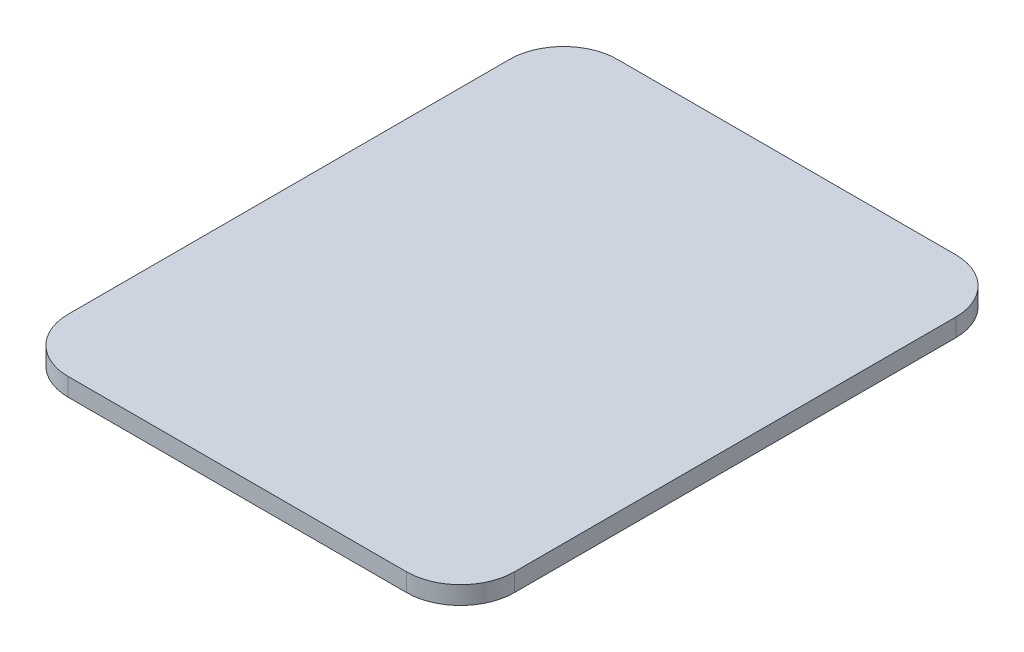
SolidWorks part; units mm, degrees
ref_plane "Front Plane" through (0, 0, 0) normal (0, 0, 1) x (1, 0, 0)
ref_plane "Top Plane" through (0, 0, 0) normal (0, 1, 0) x (1, 0, 0)
ref_plane "Right Plane" through (0, 0, 0) normal (1, 0, 0) x (0, 0, -1)
sketch "Sketch2" plane through (0, 0, 0) normal (0, 1, 0) x (1, 0, 0)
  line L0 (-46.2289, -76.7065) -> (47.6761, -76.7065)
  line L1 (-61.1889, -61.7465) -> (-61.1889, 60.7335)
  line L2 (-46.2289, 75.6935) -> (47.6761, 75.6935)
  line L3 (62.6361, -61.7465) -> (62.6361, 60.7335)
  line L4 (-61.1889, -76.7065) -> (62.6361, 75.6935) construction
  line L5 (-61.1889, 75.6935) -> (62.6361, -76.7065) construction
  arc A0 (47.6761, 75.6935) -> (62.6361, 60.7335) centre (47.6761, 60.7335) cw
  arc A1 (-61.1889, 60.7335) -> (-46.2289, 75.6935) centre (-46.2289, 60.7335) cw
  arc A2 (-46.2289, -76.7065) -> (-61.1889, -61.7465) centre (-46.2289, -61.7465) cw
  arc A3 (47.6761, -76.7065) -> (62.6361, -61.7465) centre (47.6761, -61.7465) ccw
  point P0 (0.7236, -0.5065)
extrude "Boss-Extrude1" add sketch "Sketch2" along normal blind 5
sketch "Sketch3" plane through (0, 5, 0) normal (0, 1, 0) x (1, 0, 0)
  line L0 (62.6361, -61.7465) -> (62.6361, 60.7335) construction
  line L5 (36.5711, 49.6435) -> (50.5711, 49.6435)
  line L6 (36.5711, 49.6435) -> (36.5711, 63.6435)
  line L7 (36.5711, 63.6435) -> (50.5711, 63.6435)
  line L8 (50.5711, 49.6435) -> (50.5711, 63.6435)
  line L9 (36.5711, 49.6435) -> (50.5711, 63.6435) construction
  line L10 (36.5711, 63.6435) -> (50.5711, 49.6435) construction
  line L11 (47.6761, 75.6935) -> (-46.2289, 75.6935) construction
  line L12 (36.5711, 56.6435) -> (31.5211, 56.6435) construction
  line L13 (17.5211, 49.6435) -> (31.5211, 49.6435)
  line L14 (17.5211, 49.6435) -> (17.5211, 63.6435)
  line L15 (17.5211, 63.6435) -> (31.5211, 63.6435)
  line L16 (31.5211, 49.6435) -> (31.5211, 63.6435)
  line L17 (17.5211, 56.6435) -> (12.4711, 56.6435) construction
  line L18 (-1.5289, 49.6435) -> (12.4711, 49.6435)
  line L19 (-1.5289, 49.6435) -> (-1.5289, 63.6435)
  line L20 (-1.5289, 63.6435) -> (12.4711, 63.6435)
  line L21 (12.4711, 49.6435) -> (12.4711, 63.6435)
  line L22 (-1.5289, 56.6435) -> (-6.5789, 56.6435) construction
  line L23 (-20.5789, 49.6435) -> (-6.5789, 49.6435)
  line L24 (-20.5789, 49.6435) -> (-20.5789, 63.6435)
  line L25 (-20.5789, 63.6435) -> (-6.5789, 63.6435)
  line L26 (-6.5789, 49.6435) -> (-6.5789, 63.6435)
  line L27 (-13.5789, 49.6435) -> (-13.5789, 20.4935) construction
  line L28 (-49.1539, 49.6435) -> (-35.1539, 49.6435)
  line L29 (-49.1539, 49.6435) -> (-49.1539, 63.6435)
  line L30 (-49.1539, 63.6435) -> (-35.1539, 63.6435)
  line L31 (-35.1539, 49.6435) -> (-35.1539, 63.6435)
  line L32 (43.5711, 49.6435) -> (43.5711, 20.4935) construction
  line L33 (-13.5789, 35.0685) -> (43.5711, 35.0685) construction
  line L34 (-13.5789, 35.0685) -> (43.2529, 35.0685) construction
  line L35 (36.2246, 28.0266) -> (50.2246, 28.0266)
  line L36 (36.2246, 28.0266) -> (36.2246, 42.0266)
  line L37 (36.2246, 42.0266) -> (50.2246, 42.0266)
  line L38 (50.2246, 28.0266) -> (50.2246, 42.0266)
  line L39 (36.2246, 28.0266) -> (50.2246, 42.0266) construction
  line L40 (36.2246, 42.0266) -> (50.2246, 28.0266) construction
  line L41 (36.2246, 35.0266) -> (31.1746, 35.0266) construction
  line L42 (17.1746, 28.0266) -> (31.1746, 28.0266)
  line L43 (17.1746, 28.0266) -> (17.1746, 42.0266)
  line L44 (17.1746, 42.0266) -> (31.1746, 42.0266)
  line L45 (31.1746, 28.0266) -> (31.1746, 42.0266)
  line L46 (17.1746, 35.0266) -> (12.1246, 35.0266) construction
  line L47 (-1.8754, 28.0266) -> (12.1246, 28.0266)
  line L48 (-1.8754, 28.0266) -> (-1.8754, 42.0266)
  line L49 (-1.8754, 42.0266) -> (12.1246, 42.0266)
  line L50 (12.1246, 28.0266) -> (12.1246, 42.0266)
  line L51 (-1.8754, 35.0266) -> (-6.9254, 35.0266) construction
  line L52 (-20.9254, 28.335) -> (-6.9254, 28.335)
  line L53 (-20.9254, 28.335) -> (-20.9254, 42.335)
  line L54 (-20.9254, 42.335) -> (-6.9254, 42.335)
  line L55 (-6.9254, 28.335) -> (-6.9254, 42.335)
  point P0 (43.5711, 56.6435)
  point P39 (43.2246, 35.0266)
  dimension "D1" = 14
  dimension "D2" = 14
  dimension "D3" = 12.065
  dimension "D4" = 12.05
  dimension "D5" = 5.05
  dimension "D6" = 5.05
  dimension "D7" = 5.05
  dimension "D8" = 14
  dimension "D9" = 14
  dimension "D10" = 14
  dimension "D11" = 12.05
  dimension "D12" = 12.05
  dimension "D13" = 12.05
  dimension "D14" = 14
  dimension "D15" = 14
  dimension "D16" = 14
  dimension "D17" = 14
  dimension "D18" = 14
  dimension "D19" = 14.575
  dimension "D20" = 12.05
  dimension "D21" = 14.575
  dimension "D22" = 14
  dimension "D23" = 14
  dimension "D24" = 5.05
  dimension "D25" = 5.05
  dimension "D26" = 5.05
  dimension "D27" = 14
  dimension "D28" = 14
  dimension "D29" = 14
  dimension "D30" = 14
  dimension "D31" = 14
